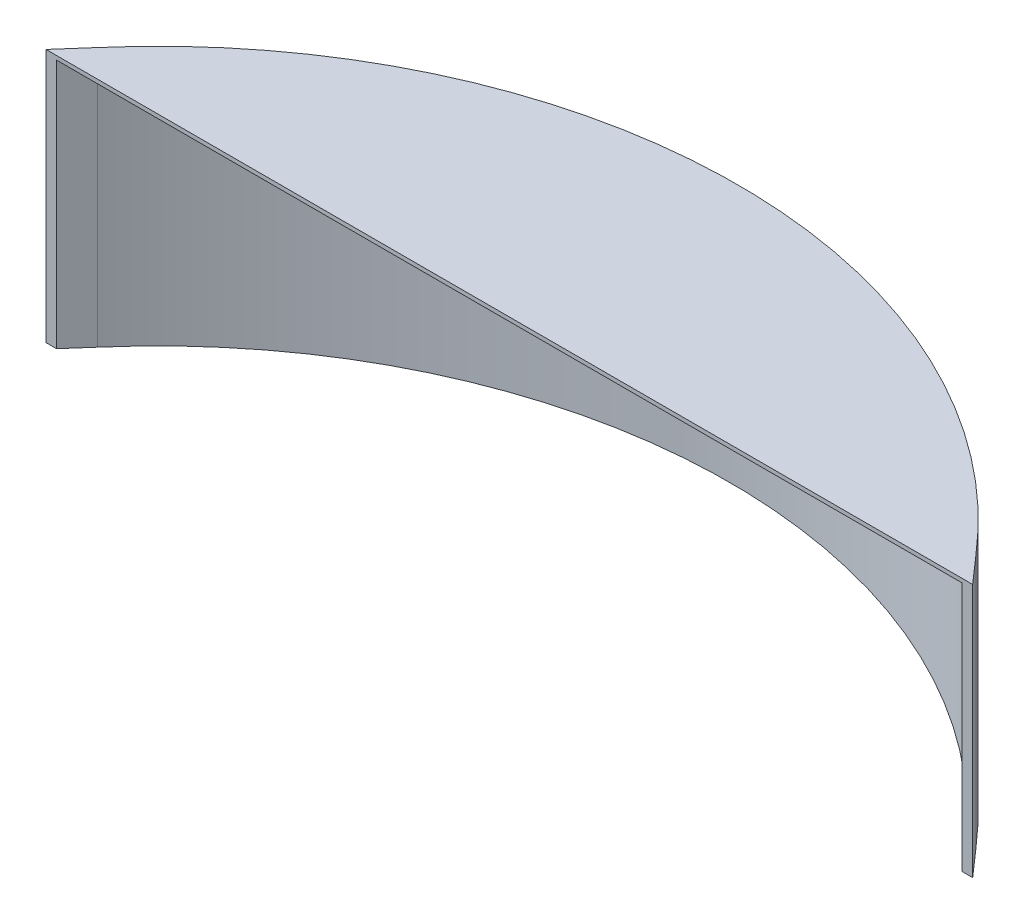
SolidWorks part; units mm, degrees
ref_plane "Front Plane" through (0, 0, 0) normal (0, 0, 1) x (1, 0, 0)
ref_plane "Top Plane" through (0, 0, 0) normal (0, 1, 0) x (1, 0, 0)
ref_plane "Right Plane" through (0, 0, 0) normal (1, 0, 0) x (0, 0, -1)
sketch "Sketch3" plane through (0, 0, 0) normal (0, 1, 0) x (1, 0, 0)
  line L0 (-117.5045, 326.1556) -> (-111.5092, 332.9711)
  line L1 (117.5045, 326.1556) -> (111.5092, 332.9711)
  line L2 (-117.5045, 326.1556) -> (117.5045, 326.1556)
  arc A0 (-111.5092, 332.9711) -> (111.5092, 332.9711) centre (0, 237.0979) cw
extrude "Boss-Extrude1" add sketch "Sketch3" along normal blind 1
sketch "Sketch4" plane through (0, 0, 0) normal (0, -1, 0) x (1, 0, 0)
  line L0 (-117.5045, -326.1556) -> (-111.5092, -332.9711)
  line L1 (117.5045, -326.1556) -> (111.5092, -332.9711)
  line L2 (-114.8408, -326.1556) -> (-110, -331.6587)
  line L4 (114.8408, -326.1556) -> (110, -331.6587)
  line L6 (-116.0028, -324.8347) -> (-110, -331.6587) construction
  line L8 (116.0028, -324.8347) -> (110, -331.6587) construction
  line L10 (114.8408, -326.1556) -> (117.5045, -326.1556)
  line L11 (-117.5045, -326.1556) -> (-114.8408, -326.1556)
  arc A0 (-111.5092, -332.9711) -> (111.5092, -332.9711) centre (0, -237.0979) ccw
  arc A1 (-110, -331.6587) -> (110, -331.6587) centre (0, -237.0979) ccw
  dimension "D1" = 2
extrude "Boss-Extrude2" add sketch "Sketch4" along normal blind 63.4
equation "\"gap\"= 1mm"
equation "\"casewidth\"= 2mm"
